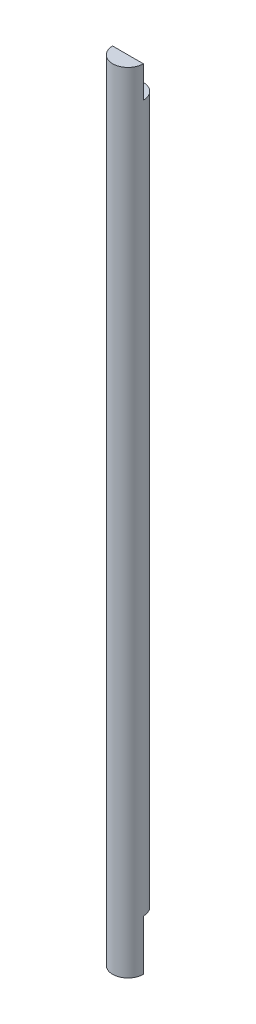
SolidWorks part; units mm, degrees
material "Thornel Mat VMA"
ref_plane "Front Plane" through (0, 0, 0) normal (0, 0, 1) x (1, 0, 0)
ref_plane "Top Plane" through (0, 0, 0) normal (0, 1, 0) x (1, 0, 0)
ref_plane "Right Plane" through (0, 0, 0) normal (1, 0, 0) x (0, 0, -1)
sketch "Sketch1" plane through (0, 0, 0) normal (0, 1, 0) x (1, 0, 0)
  circle A0 centre (0, 0) radius 1.95
  dimension "D1" = 3.9
extrude "Boss-Extrude1" add sketch "Sketch1" along normal mid plane 100
sketch "Sketch2" plane through (0, 0, 0) normal (0, 0, 1) x (1, 0, 0)
  line L0 (1.95, 50) -> (-1.95, 50) construction
  line L1 (-1.95, 50) -> (1.95, 50)
  line L2 (-1.95, 50) -> (-1.95, 46)
  line L3 (-1.95, 46) -> (1.95, 46)
  line L4 (1.95, 50) -> (1.95, 46)
  line L5 (-1.95, -50) -> (1.95, -50)
  line L6 (-1.95, -50) -> (-1.95, -43.6)
  line L7 (-1.95, -43.6) -> (1.95, -43.6)
  line L8 (1.95, -50) -> (1.95, -43.6)
  line L11 (-1.95, -50) -> (1.95, -50) construction
  line L12 (1.95, -50) -> (1.95, 50) construction
  line L13 (-1.95, 50) -> (-1.95, -50) construction
  dimension "D1" = 6.4
  dimension "D2" = 4
extrude "Cut-Extrude1" cut sketch "Sketch2" against normal through all
